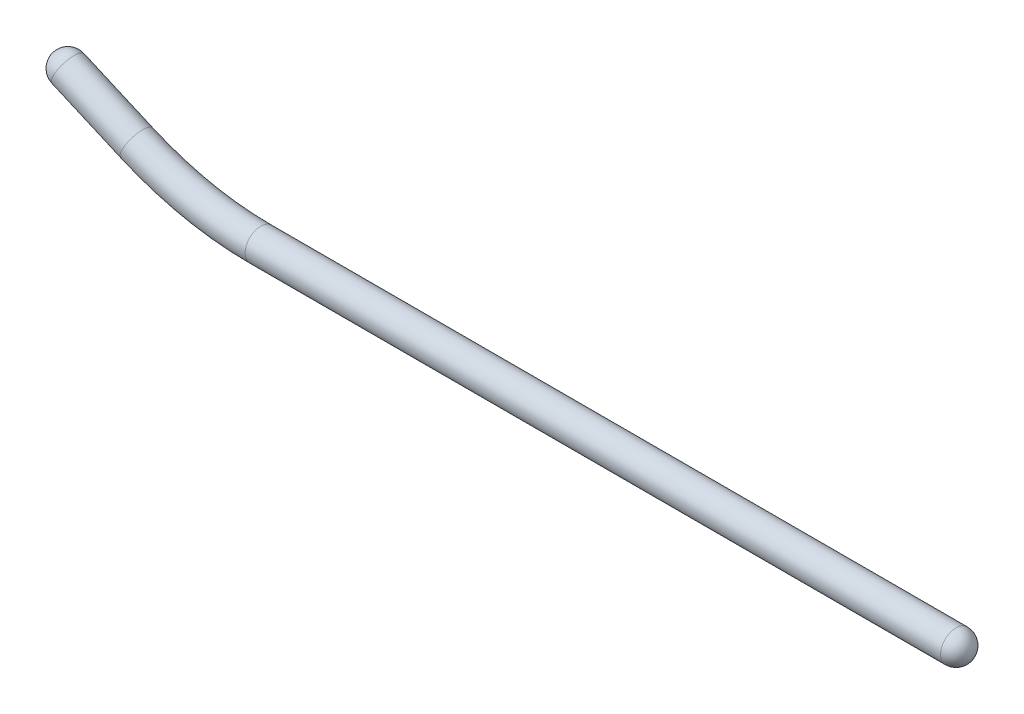
SolidWorks part; units mm, degrees
ref_plane "Front Plane" through (0, 0, 0) normal (0, 0, 1) x (1, 0, 0)
ref_plane "Top Plane" through (0, 0, 0) normal (0, 1, 0) x (1, 0, 0)
ref_plane "Right Plane" through (0, 0, 0) normal (1, 0, 0) x (0, 0, -1)
sketch "Sketch1" plane through (0, 0, 0) normal (0, 0, 1) x (1, 0, 0)
  line L0 (0, 0) -> (-45.8258, 0)
  line L1 (-53.8258, 1.6697) -> (-59.1652, 4)
  arc A0 (-45.8258, 0) -> (-53.8258, 1.6697) centre (-45.8258, 20) cw
  point P6 (-50, 0)
  dimension "D4" = 20
  dimension "D1" = 50
  dimension "D2" = 10
  dimension "D3" = 4
sketch "Sketch2" plane through (0, 0, 0) normal (1, 0, 0) x (0, 0, -1)
  circle A0 centre (0, 0) radius 1
  dimension "D1" = 2
sweep "Sweep1" add profiles "Sketch2" path "Sketch1"
fillet "Fillet1" radius 1 2 edges at (-59.1652, 4, -1) (0, 0, -1)
